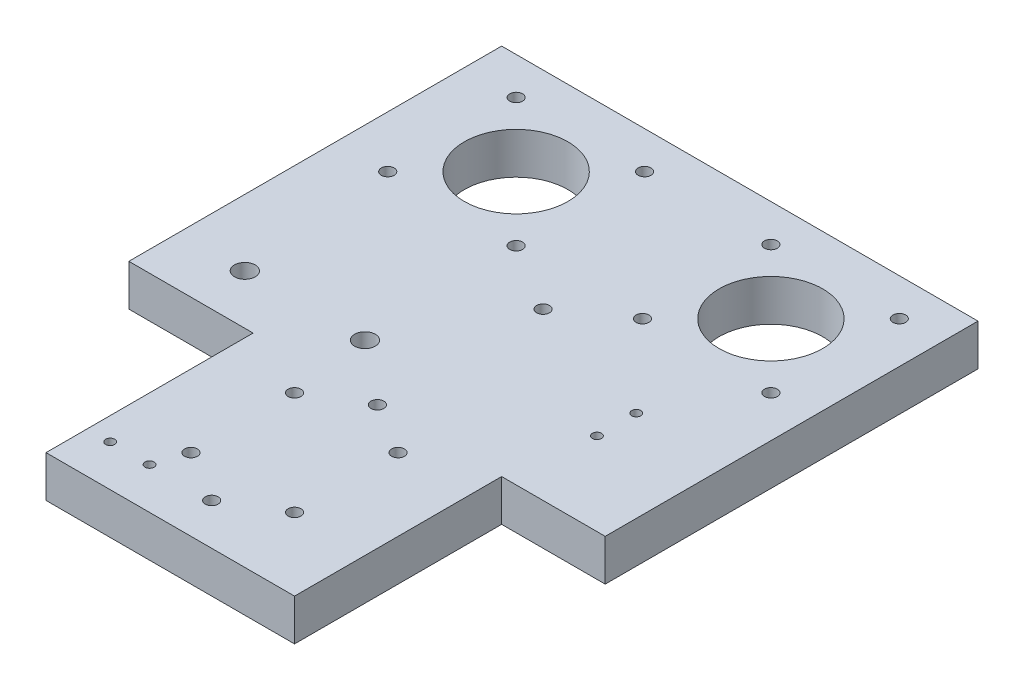
SolidWorks part; units mm, degrees
ref_plane "Front" through (0, 0, 0) normal (0, 0, 1) x (1, 0, 0)
ref_plane "Top" through (0, 0, 0) normal (0, 1, 0) x (1, 0, 0)
ref_plane "Right" through (0, 0, 0) normal (1, 0, 0) x (0, 0, -1)
sketch "Sketch1" plane through (0, 0, 0) normal (0, 1, 0) x (1, 0, 0)
  line L1 (-30, -70) -> (30, -70)
  line L2 (-30, -70) -> (-30, 70)
  line L3 (-30, 70) -> (30, 70)
  line L4 (30, -70) -> (30, 70)
  line L5 (-30, -70) -> (30, 70) construction
  line L6 (-30, 70) -> (30, -70) construction
  point P0 (0, 0)
  dimension "D1" = 140
  dimension "D2" = 60
extrude "Boss-Extrude1" add sketch "Sketch1" along normal blind 10
sketch "Sketch3" plane through (0, 10, 0) normal (0, 1, 0) x (1, 0, 0)
  line L0 (-30, -70) -> (30, -70) construction
  circle A0 centre (0, -60) radius 1.55
  circle A1 centre (0, -20) radius 1.55
  circle A2 centre (0, 20) radius 1.55
  dimension "D1" = 3.1
  dimension "D2" = 3.1
  dimension "D3" = 3.1
  dimension "D4" = 10
  dimension "D5" = 40
  dimension "D6" = 40
extrude "Cut-Extrude1" cut sketch "Sketch3" against normal through all
sketch "Sketch4" plane through (0, 10, 0) normal (0, 1, 0) x (1, 0, 0)
  line L1 (-12.5, -52.5) -> (12.5, -52.5) construction
  line L2 (-12.5, -52.5) -> (-12.5, -27.5) construction
  line L3 (-12.5, -27.5) -> (12.5, -27.5) construction
  line L4 (12.5, -52.5) -> (12.5, -27.5) construction
  line L5 (-12.5, -52.5) -> (12.5, -27.5) construction
  line L6 (-12.5, -27.5) -> (12.5, -52.5) construction
  circle A0 centre (12.5, -27.5) radius 1.55
  circle A1 centre (12.5, -52.5) radius 1.55
  circle A2 centre (-12.5, -27.5) radius 1.55
  circle A3 centre (-12.5, -52.5) radius 1.55
  circle A6 centre (0, -20) radius 1.55 construction
  point P0 (0, -40)
  dimension "D2" = 3.1
  dimension "D3" = 3.1
  dimension "D4" = 3.1
  dimension "D5" = 3.1
  dimension "D6" = 20
  dimension "D1" = 25
extrude "Cut-Extrude2" cut sketch "Sketch4" against normal through all
sketch "Sketch7" plane through (0, 10, 0) normal (0, 1, 0) x (1, 0, 0)
  line L1 (30, 70) -> (55, 70)
  line L2 (30, 70) -> (30, -20)
  line L3 (30, -20) -> (55, -20)
  line L4 (55, 70) -> (55, -20)
  line L5 (30, 70) -> (55, -20) construction
  line L6 (30, -20) -> (55, 70) construction
  point P4 (42.5, 25)
  dimension "D1" = 25
  dimension "D2" = 90
extrude "Boss-Extrude2" add sketch "Sketch7" against normal up to surface (10 mm away) up to face at (12.5, 0, 54.05)
sketch "Sketch8" plane through (0, 10, 0) normal (0, 1, 0) x (1, 0, 0)
  line L1 (14, 30) -> (45, 30) construction
  line L2 (14, 30) -> (14, 61) construction
  line L3 (14, 61) -> (45, 61) construction
  line L4 (45, 30) -> (45, 61) construction
  line L5 (14, 30) -> (45, 61) construction
  line L6 (14, 61) -> (45, 30) construction
  circle A0 centre (14, 30) radius 1.55
  circle A1 centre (45, 30) radius 1.55
  circle A2 centre (45, 61) radius 1.55
  circle A3 centre (14, 61) radius 1.55
  circle A4 centre (29.5, 45.5) radius 12.5
  point P0 (29.5, 45.5)
  dimension "D4" = 3.1
  dimension "D5" = 3.1
  dimension "D6" = 3.1
  dimension "D7" = 3.1
  dimension "D8" = 25
  dimension "D1" = 31
  dimension "D2" = 29.5
  dimension "D3" = 30
extrude "Cut-Extrude4" cut sketch "Sketch8" against normal through all
sketch "Sketch9" plane through (0, 10, 0) normal (0, 1, 0) x (1, 0, 0)
  line L1 (-30, 70) -> (-60, 70)
  line L2 (-30, 70) -> (-30, -20)
  line L3 (-30, -20) -> (-60, -20)
  line L4 (-60, 70) -> (-60, -20)
  line L5 (-30, 70) -> (-60, -20) construction
  line L6 (-30, -20) -> (-60, 70) construction
  point P4 (-45, 25)
  dimension "D1" = 90
  dimension "D2" = 30
extrude "Boss-Extrude3" add sketch "Sketch9" against normal up to surface (10 mm away) up to face at (29.5, 0, -33)
sketch "Sketch10" plane through (0, 10, 0) normal (0, 1, 0) x (1, 0, 0)
  line L1 (-47.5, 61) -> (-16.5, 61) construction
  line L2 (-47.5, 61) -> (-47.5, 30) construction
  line L3 (-47.5, 30) -> (-16.5, 30) construction
  line L4 (-16.5, 61) -> (-16.5, 30) construction
  line L5 (-47.5, 61) -> (-16.5, 30) construction
  line L6 (-47.5, 30) -> (-16.5, 61) construction
  circle A1 centre (-47.5, 61) radius 1.55
  circle A2 centre (-16.5, 61) radius 1.55
  circle A3 centre (-16.5, 30) radius 1.55
  circle A4 centre (-47.5, 30) radius 1.55
  circle A5 centre (-32, 45.5) radius 12.5
  point P0 (-32, 45.5)
  dimension "D4" = 3.1
  dimension "D5" = 3.1
  dimension "D6" = 3.1
  dimension "D7" = 3.1
  dimension "D8" = 25
  dimension "D1" = 31
  dimension "D2" = 30
  dimension "D3" = 32
extrude "Cut-Extrude5" cut sketch "Sketch10" against normal through all
sketch "Sketch11" plane through (0, 10, 0) normal (0, 1, 0) x (1, 0, 0)
  line L1 (-60, 70) -> (-60, -20) construction
  circle A0 centre (-44, -8) radius 2.5
  circle A1 centre (-15, -8) radius 2.5
  dimension "D1" = 5
  dimension "D3" = 12
  dimension "D4" = 5
  dimension "D5" = 15
  dimension "D2" = 16
extrude "Cut-Extrude6" cut sketch "Sketch11" against normal through all
sketch "Sketch12" plane through (0, 10, 0) normal (0, 1, 0) x (1, 0, 0)
  line L0 (-30, -70) -> (30, -70) construction
  line L1 (-30, -20) -> (-30, -70) construction
  circle A0 centre (-24.5, -60) radius 1.1
  circle A1 centre (-15, -60) radius 1.1
  dimension "D1" = 2.2
  dimension "D2" = 2.2
  dimension "D4" = 5.5
  dimension "D5" = 9.5
  dimension "D3" = 10
extrude "Cut-Extrude7" cut sketch "Sketch12" against normal through all
sketch "Sketch13" plane through (0, 0, 0) normal (0, -1, 0) x (1, 0, 0)
  line L0 (30, 20) -> (55, 20) construction
  line L1 (55, 20) -> (55, -70) construction
  circle A0 centre (33, -9.5) radius 1.1
  circle A1 centre (33, 0) radius 1.1
  dimension "D1" = 2.2
  dimension "D2" = 2.2
  dimension "D5" = 22
  dimension "D3" = 9.5
  dimension "D4" = 20
extrude "Cut-Extrude8" cut sketch "Sketch13" against normal up to next
